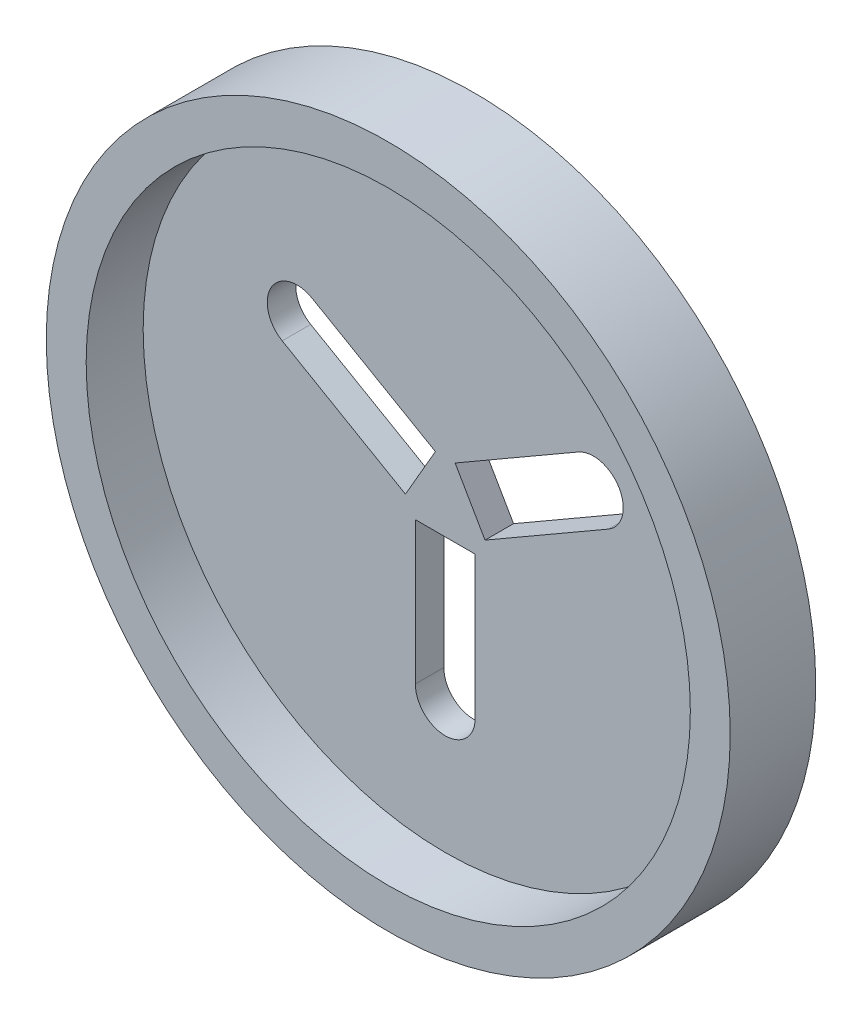
SolidWorks part; units mm, degrees
ref_plane "Alzado" through (0, 0, 0) normal (0, 0, 1) x (1, 0, 0)
ref_plane "Planta" through (0, 0, 0) normal (0, 1, 0) x (1, 0, 0)
ref_plane "Vista lateral" through (0, 0, 0) normal (1, 0, 0) x (0, 0, -1)
sketch "Croquis1" plane through (0, 0, 0) normal (0, 0, 1) x (1, 0, 0)
  circle A0 centre (0, 0) radius 55
  dimension "D1" = 110
extrude "Disco" add sketch "Croquis1" along normal blind 5
sketch "Croquis6" plane through (0, 0, 5) normal (0, 0, 1) x (1, 0, 0)
  line L0 (-5.25, 0) -> (-5.25, -30)
  line L1 (5.25, 0) -> (5.25, -30)
  line L2 (2.625, 4.5466) -> (-23.3558, 19.5466)
  line L3 (-2.625, -4.5466) -> (-28.6058, 10.4534)
  line L4 (2.625, -4.5466) -> (28.6058, 10.4534)
  line L5 (-2.625, 4.5466) -> (23.3558, 19.5466)
  arc A1 (-5.25, 0) -> (5.25, 0) centre (0, 0) cw
  arc A2 (-5.25, -30) -> (5.25, -30) centre (0, -30) ccw
  arc A3 (2.625, 4.5466) -> (-2.625, -4.5466) centre (0, 0) cw
  arc A4 (-23.3558, 19.5466) -> (-28.6058, 10.4534) centre (-25.9808, 15) ccw
  arc A5 (2.625, -4.5466) -> (-2.625, 4.5466) centre (0, 0) cw
  arc A6 (28.6058, 10.4534) -> (23.3558, 19.5466) centre (25.9808, 15) ccw
  point P22 (0, 0)
  dimension "D1" = 30
  dimension "D3" = 5.25
  dimension "D2" = 3
extrude "Cortar-Extruir1" cut sketch "Croquis6" against normal blind 10 contours L2 A4 L3 A3 | L5 A6 L4 A5 | L1 A2 L0 A1
sketch "Croquis7" plane through (0, 0, 5) normal (0, 0, 1) x (1, 0, 0)
  circle A0 centre (0, 0) radius 53
  circle A1 centre (0, 0) radius 60
  circle A2 centre (0, 0) radius 53
  circle M3 centre (0, 0) radius 55
  dimension "D1" = 120
  dimension "D2" = 106
extrude "Saliente-Extruir1" add sketch "Croquis7" along normal blind 10 and the other way through all contours A0 M3 | A1 M3
sketch "Croquis8" plane through (0, 0, 5) normal (0, 0, 1) x (1, 0, 0)
  line L3 (-8.7141, -5.0311) -> (0, 10.0622)
  line L4 (0, 10.0622) -> (8.7141, -5.0311)
  line L5 (8.7141, -5.0311) -> (-8.7141, -5.0311)
extrude "Saliente-Extruir6" add sketch "Croquis8" against normal blind 5
